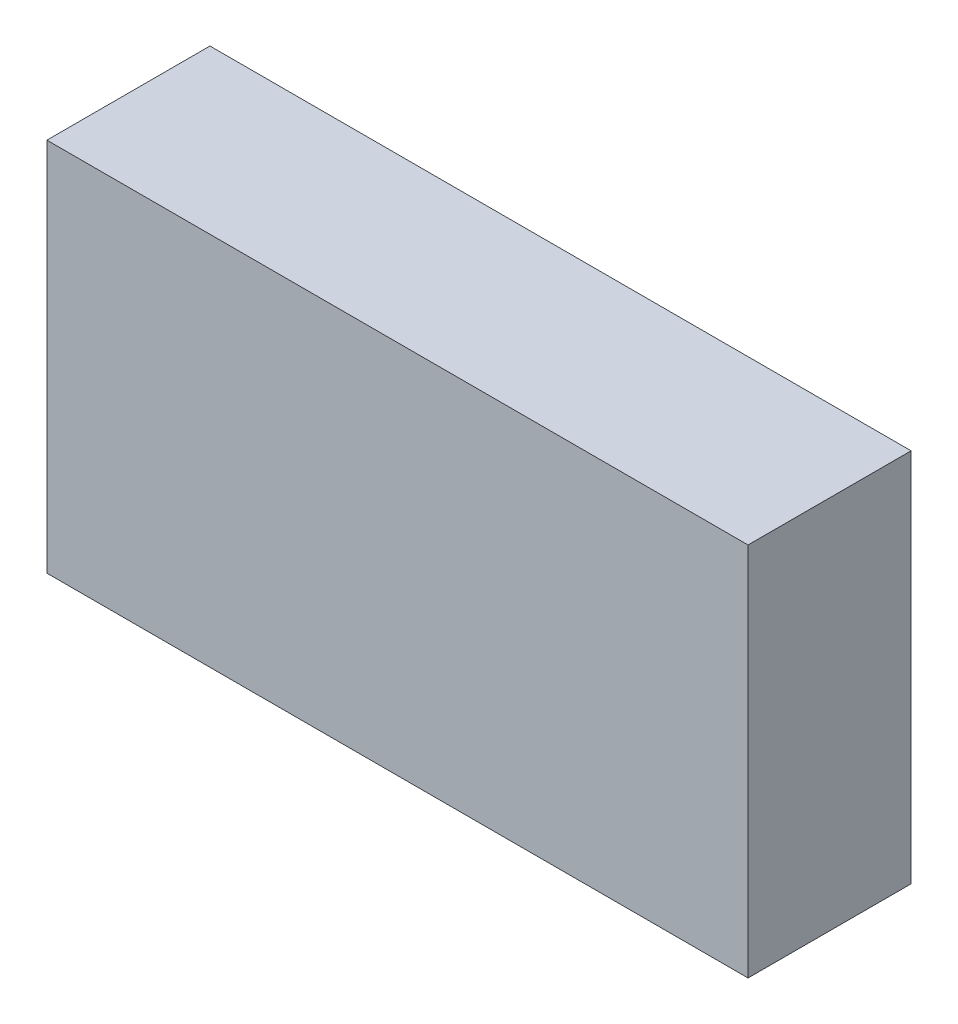
SolidWorks part; units mm, degrees
ref_plane "Płaszczyzna przednia" through (0, 0, 0) normal (0, 0, 1) x (1, 0, 0)
ref_plane "Płaszczyzna górna" through (0, 0, 0) normal (0, 1, 0) x (1, 0, 0)
ref_plane "Płaszczyzna prawa" through (0, 0, 0) normal (1, 0, 0) x (0, 0, -1)
sketch "Szkic1" plane through (0, 0, 0) normal (0, 0, 1) x (1, 0, 0)
  line L1 (0, 0) -> (215, 0)
  line L2 (0, 0) -> (0, 115)
  line L3 (0, 115) -> (215, 115)
  line L4 (215, 0) -> (215, 115)
  dimension "D1" = 215
  dimension "D2" = 115
extrude "Dodanie-wyciągnięcie1" add sketch "Szkic1" along normal blind 50
